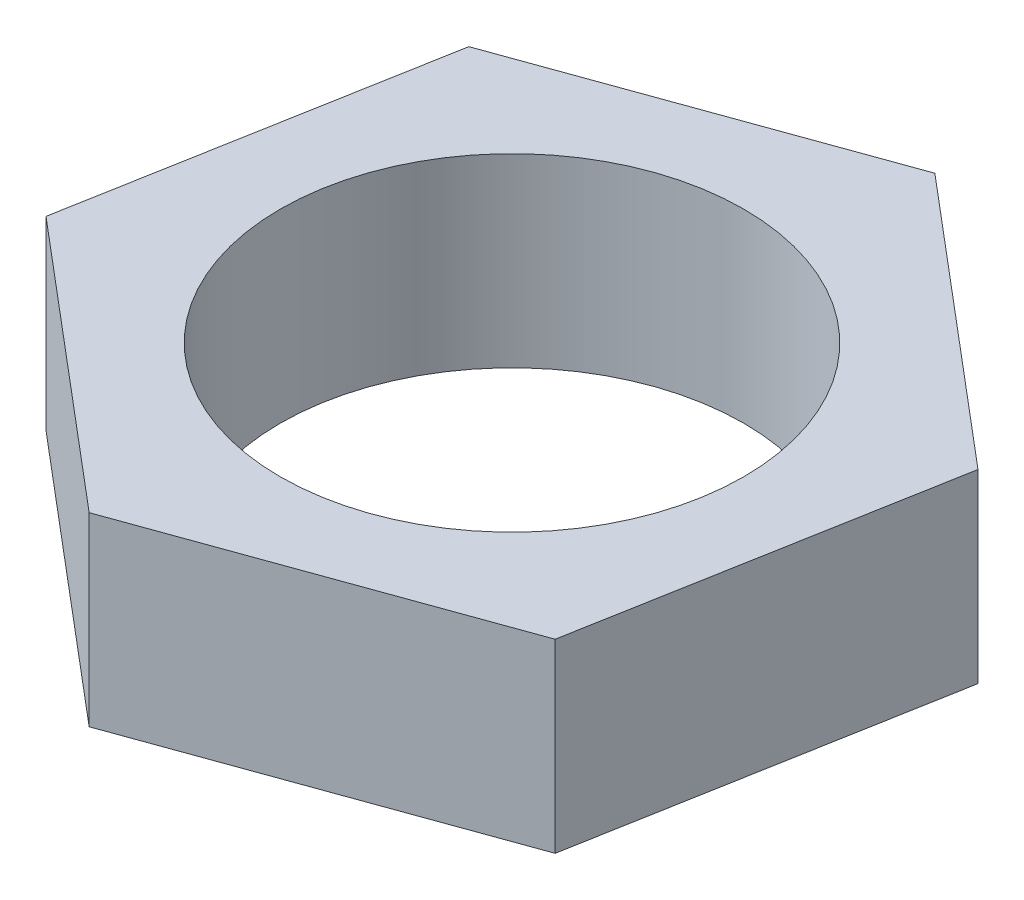
SolidWorks part; units mm, degrees
material "2219-T87"
ref_plane "前视基准面" through (0, 0, 0) normal (0, 0, 1) x (1, 0, 0)
ref_plane "上视基准面" through (0, 0, 0) normal (0, 1, 0) x (1, 0, 0)
ref_plane "右视基准面" through (0, 0, 0) normal (1, 0, 0) x (0, 0, -1)
other "Configuration Table"
sketch "草图1" plane through (0, 0, 0) normal (0, 1, 0) x (1, 0, 0)
  line L1 (3.695, 1.3308) -> (0.695, 3.8654)
  line L2 (0.695, 3.8654) -> (-3, 2.5346)
  line L3 (-3, 2.5346) -> (-3.695, -1.3308)
  line L4 (-3.695, -1.3308) -> (-0.695, -3.8654)
  line L5 (-0.695, -3.8654) -> (3, -2.5346)
  line L6 (3, -2.5346) -> (3.695, 1.3308)
  circle A0 centre (0, 0) radius 3.4012 construction
  circle A1 centre (0, 0) radius 2.5
  dimension "D1" = 5
  dimension "D2" = 3
  dimension "D3" = 6.4
extrude "凸台-拉伸1" add sketch "草图1" along normal blind 2
